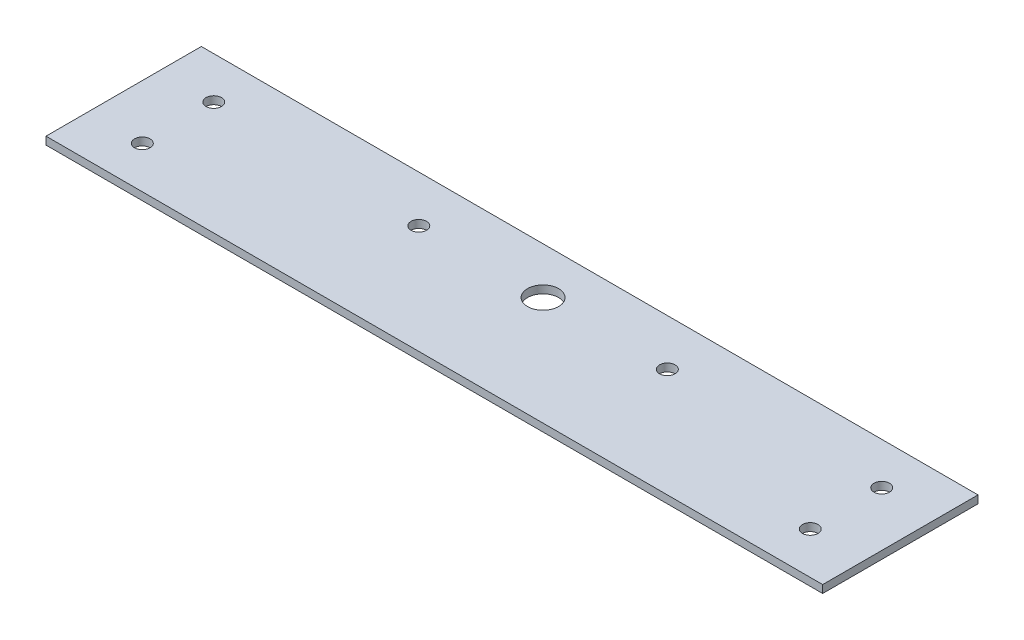
SolidWorks part; units mm, degrees
ref_plane "Front Plane" through (0, 0, 0) normal (0, 0, 1) x (1, 0, 0)
ref_plane "Top Plane" through (0, 0, 0) normal (0, 1, 0) x (1, 0, 0)
ref_plane "Right Plane" through (0, 0, 0) normal (1, 0, 0) x (0, 0, -1)
sketch "Sketch1" plane through (0, 0, 0) normal (0, 1, 0) x (1, 0, 0)
  line L1 (0, 0) -> (500, 0)
  line L2 (0, 0) -> (0, 100)
  line L3 (0, 100) -> (500, 100)
  line L4 (500, 0) -> (500, 100)
  dimension "D1" = 500
  dimension "D2" = 100
extrude "Boss-Extrude1" add sketch "Sketch1" along normal blind 5 contours L3 L4 L1 L2
sketch "Sketch3" plane through (0, 5, 0) normal (0, 1, 0) x (1, 0, 0)
  circle A0 centre (250, 70) radius 10
extrude "Cut-Extrude1" cut sketch "Sketch3" against normal through all
sketch "Sketch4" plane through (0, 5, 0) normal (0, 1, 0) x (1, 0, 0)
  circle A0 centre (170, 70) radius 5
extrude "Cut-Extrude2" cut sketch "Sketch4" against normal through all
sketch "Sketch5" plane through (0, 5, 0) normal (0, 1, 0) x (1, 0, 0)
  circle A0 centre (330, 70) radius 5
extrude "Cut-Extrude3" cut sketch "Sketch5" against normal through all
sketch "Sketch7" plane through (0, 0, 0) normal (0, -1, 0) x (-1, 0, 0)
  circle A0 centre (-465, 73) radius 5
  circle A1 centre (-465, 27) radius 5
  circle A2 centre (-35, 27) radius 5
  circle A3 centre (-35, 73) radius 5
  point P2 (-474.4242, 78.5983)
  point P3 (-474.4202, 28.8452)
  point P10 (-35.6295, 74.8452)
  point P11 (-35.6295, 22.3134)
  point P12 (0, 0)
  point P13 (0, 0)
  point P14 (0, 0)
  point P15 (0, 0)
  point P16 (0, 0)
  dimension "D2" = 46
extrude "Cut-Extrude4" cut sketch "Sketch7" against normal through all
